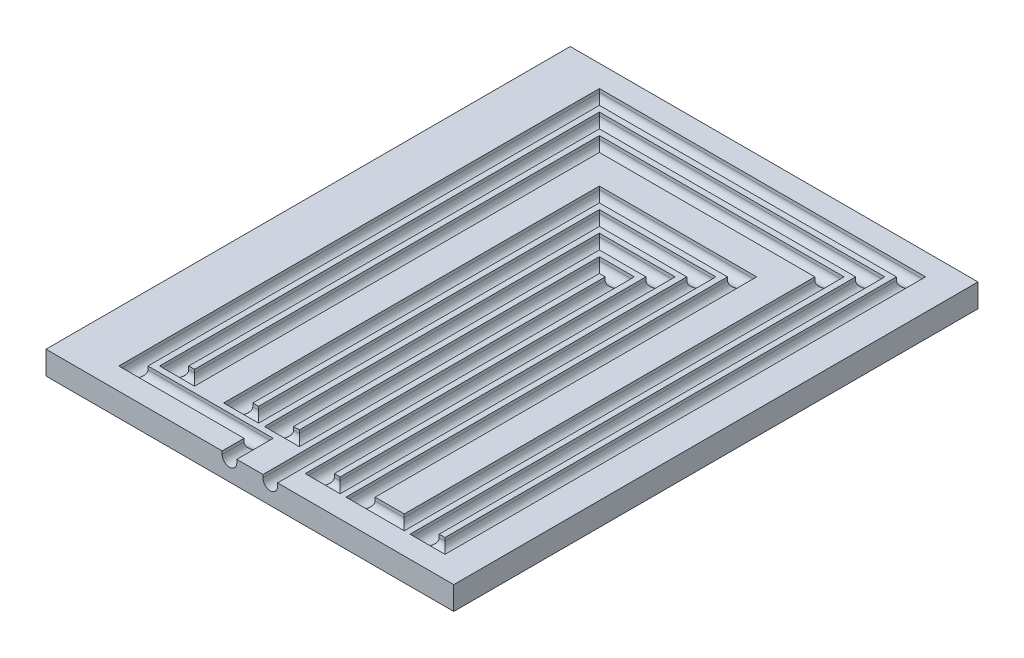
SolidWorks part; units mm, degrees
ref_plane "Front Plane" through (0, 0, 0) normal (0, 0, 1) x (1, 0, 0)
ref_plane "Top Plane" through (0, 0, 0) normal (0, 1, 0) x (1, 0, 0)
ref_plane "Right Plane" through (0, 0, 0) normal (1, 0, 0) x (0, 0, -1)
sketch "Sketch1" plane through (0, 0, 0) normal (0, 1, 0) x (1, 0, 0)
  line L1 (-88.9, -114.3) -> (88.9, -114.3)
  line L2 (-88.9, -114.3) -> (-88.9, 114.3)
  line L3 (-88.9, 114.3) -> (88.9, 114.3)
  line L4 (88.9, -114.3) -> (88.9, 114.3)
  line L5 (-88.9, -114.3) -> (88.9, 114.3) construction
  line L6 (-88.9, 114.3) -> (88.9, -114.3) construction
  point P0 (0, 0)
  dimension "D1" = 177.8
  dimension "D2" = 228.6
extrude "Boss-Extrude1" add sketch "Sketch1" along normal blind 10.16
sketch "Sketch2" plane through (0, 10.16, 0) normal (0, 1, 0) x (1, 0, 0)
  line L0 (0, -114.3) -> (0, 114.3) construction
  line L1 (-88.9, -114.3) -> (88.9, -114.3) construction
  line L2 (88.9, 114.3) -> (-88.9, 114.3) construction
  line L3 (-88.9, 0) -> (88.9, 0) construction
  line L4 (-88.9, 114.3) -> (-88.9, -114.3) construction
  line L5 (88.9, -114.3) -> (88.9, 114.3) construction
  line L6 (8.89, -114.3) -> (8.89, 38.1)
  line L7 (8.89, 38.1) -> (0, 38.1)
  line L8 (0, 38.1) -> (0, -92.71)
  line L9 (0, -92.71) -> (-8.89, -92.71)
  line L10 (-8.89, -92.71) -> (-8.89, 46.99)
  line L11 (-8.89, 46.99) -> (17.78, 46.99)
  line L12 (17.78, 46.99) -> (17.78, -101.6)
  line L13 (17.78, -101.6) -> (26.67, -101.6)
  line L14 (26.67, -101.6) -> (26.67, 55.88)
  line L15 (26.67, 55.88) -> (-17.78, 55.88)
  line L16 (-17.78, 55.88) -> (-17.78, -92.71)
  line L17 (-17.78, -92.71) -> (-26.67, -92.71)
  line L18 (-26.67, -92.71) -> (-26.67, 64.77)
  line L19 (-26.67, 64.77) -> (35.56, 64.77)
  line L20 (35.56, 64.77) -> (35.56, -101.6)
  line L21 (35.56, -101.6) -> (54.61, -101.6)
  line L22 (54.61, -101.6) -> (54.61, 83.82)
  line L23 (54.61, 83.82) -> (-45.72, 83.82)
  line L24 (-45.72, 83.82) -> (-45.72, -92.71)
  line L25 (-45.72, -92.71) -> (-54.61, -92.71)
  line L26 (-8.89, -101.6) -> (-8.89, -114.3)
  line L27 (-54.61, -92.71) -> (-54.61, 92.71)
  line L28 (-54.61, 92.71) -> (63.5, 92.71)
  line L29 (63.5, 92.71) -> (63.5, -101.6)
  line L30 (63.5, -101.6) -> (72.39, -101.6)
  line L31 (72.39, -101.6) -> (72.39, 101.6)
  line L32 (72.39, 101.6) -> (-63.5, 101.6)
  line L33 (-63.5, 101.6) -> (-63.5, -101.6)
  line L34 (-63.5, -101.6) -> (-8.89, -101.6)
  dimension "D1" = 8.89
  dimension "D2" = 8.89
  dimension "D3" = 19.05
  dimension "D4" = 8.89
  dimension "D5" = 8.89
  dimension "D6" = 8.89
  dimension "D7" = 8.89
  dimension "D8" = 8.89
  dimension "D9" = 8.89
  dimension "D10" = 8.89
  dimension "D11" = 19.05
  dimension "D12" = 8.89
  dimension "D13" = 8.89
  dimension "D14" = 8.89
  dimension "D15" = 8.89
  dimension "D16" = 8.89
  dimension "D17" = 8.89
  dimension "D18" = 8.89
  dimension "D19" = 19.05
  dimension "D20" = 8.89
  dimension "D21" = 8.89
  dimension "D22" = 12.7
  dimension "D23" = 12.7
  dimension "D24" = 12.7
sketch "Sketch4" plane through (0, 0, 114.3) normal (0, 0, 1) x (1, 0, 0)
  line L2 (-8.89, 10.16) -> (-8.89, 8.7609) construction
  line L3 (-5.715, 10.16) -> (-5.715, 8.7609)
  line L4 (-12.065, 10.16) -> (-12.065, 8.7609)
  arc A1 (-5.715, 10.16) -> (-12.065, 10.16) centre (-8.89, 10.16) ccw
  arc A2 (-12.065, 8.7609) -> (-5.715, 8.7609) centre (-8.89, 8.7609) ccw
  point P2 (-8.89, 9.4605)
  dimension "D1" = 3.175
sweep "Cut-Sweep2" cut profiles "Sketch4" path "Sketch2"
equation "\"Channel Diameter\"= .25in"
equation "\"Inner Channel Width\"= .75in"
equation "\"Outer Rim Width\"= .5in"
equation "\"BtwnChannel\"= .1in"
equation "\"D\"= \"Channel Diameter\" + \"BtwnChannel\""
